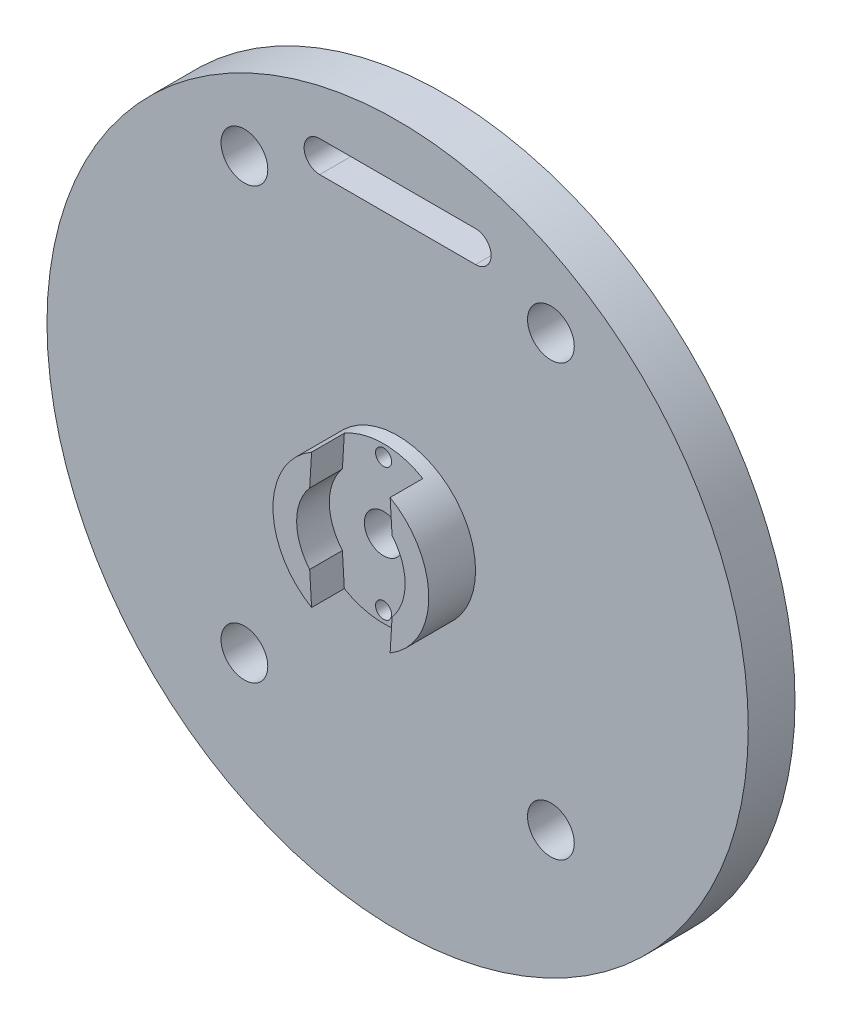
SolidWorks part; units mm, degrees
ref_plane "Plan de face" through (0, 0, 0) normal (0, 0, 1) x (1, 0, 0)
ref_plane "Plan de dessus" through (0, 0, 0) normal (0, 1, 0) x (1, 0, 0)
ref_plane "Plan de droite" through (0, 0, 0) normal (1, 0, 0) x (0, 0, -1)
sketch "Esquisse1" plane through (0, 0, 0) normal (0, 0, 1) x (1, 0, 0)
  circle A0 centre (0, 0) radius 22.5
  dimension "D1" = 45
extrude "Boss.-Extru.1" add sketch "Esquisse1" along normal blind 3
sketch "Esquisse2" plane through (0, 0, 3) normal (0, 0, 1) x (1, 0, 0)
  circle A0 centre (0, 0) radius 5
  dimension "D1" = 10
extrude "Boss.-Extru.2" add sketch "Esquisse2" along normal blind 3
sketch "Esquisse6" plane through (0, 0, 0) normal (0, 0, -1) x (-1, 0, 0)
  line L0 (0, 0) -> (0, 22.5) construction
  line L1 (-5, 18) -> (5, 18) construction
  line L2 (-5, 19) -> (5, 19)
  line L3 (-5, 17) -> (5, 17)
  circle A0 centre (0, 0) radius 22.5 construction
  arc A1 (-5, 19) -> (-5, 17) centre (-5, 18) ccw
  arc A2 (5, 17) -> (5, 19) centre (5, 18) ccw
  point P8 (0, 18)
  dimension "D3" = 10
  dimension "D1" = 18
  dimension "D2" = 2
extrude "Enlèv. mat.-Extru.3" cut sketch "Esquisse6" against normal blind 10
sketch "Esquisse10" plane through (0, 0, 0) normal (0, 0, -1) x (-1, 0, 0)
  circle A0 centre (-9.835, -12) radius 1.5
  circle A1 centre (9.8312, -12) radius 1.5
extrude "Enlèv. mat.-Extru.4" cut sketch "Esquisse10" against normal blind 10
sketch "Esquisse11" plane through (0, 0, 6) normal (0, 0, 1) x (1, 0, 0)
  line L4 (0, 8.9527) -> (0, -7.7562) construction
  line L7 (2.5166, 4.3782) -> (2.6439, 2.2628)
  line L8 (2.6439, -2.2628) -> (2.5166, -4.3782)
  line L9 (-2.6439, -2.2628) -> (-2.5166, -4.3782)
  line L10 (-2.5166, 4.3782) -> (-2.6439, 2.2628)
  arc A6 (2.6439, 2.2628) -> (2.6439, -2.2628) centre (0, 0) cw
  arc A7 (-2.5166, -4.3782) -> (2.5166, -4.3782) centre (0, 0) ccw
  arc A8 (-2.6439, 2.2628) -> (-2.6439, -2.2628) centre (0, 0) ccw
  arc A9 (2.5166, 4.3782) -> (-2.5166, 4.3782) centre (0, 0) ccw
extrude "Enlèv. mat.-Extru.5" cut sketch "Esquisse11" against normal blind 2.1
sketch "Esquisse12" plane through (0, 0, 3.9) normal (0, 0, 1) x (1, 0, 0)
  circle A0 centre (0, 4.25) radius 0.515
  circle A1 centre (0, 0) radius 1.235
  circle A2 centre (0, -4.25) radius 0.515
extrude "Enlèv. mat.-Extru.6" cut sketch "Esquisse12" against normal through all
sketch "Esquisse13" plane through (0, 0, 0) normal (0, 0, -1) x (-1, 0, 0)
  circle A0 centre (-9.835, 15.615) radius 1.5
  circle A1 centre (9.8312, 15.615) radius 1.5
extrude "Enlèv. mat.-Extru.7" cut sketch "Esquisse13" against normal through all
